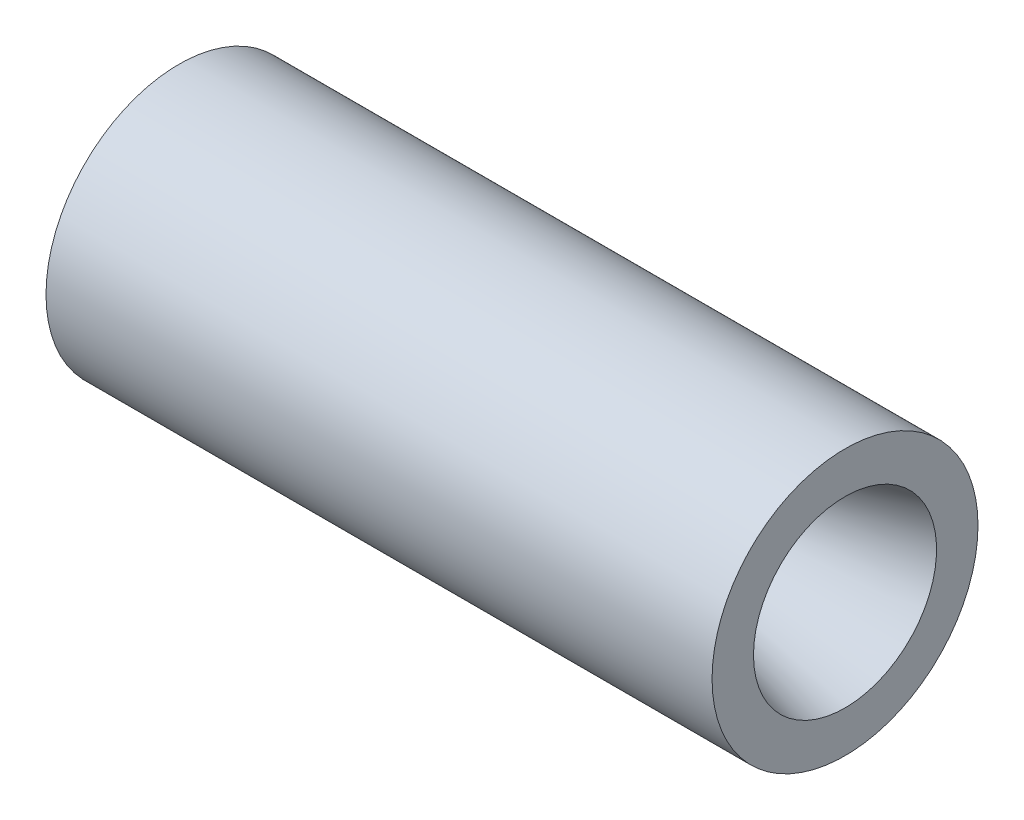
SolidWorks part; units mm, degrees
ref_plane "Front Plane" through (0, 0, 0) normal (0, 0, 1) x (1, 0, 0)
ref_plane "Top Plane" through (0, 0, 0) normal (0, 1, 0) x (1, 0, 0)
ref_plane "Right Plane" through (0, 0, 0) normal (1, 0, 0) x (0, 0, -1)
sketch "Sketch1" plane through (0, 0, 0) normal (0, 0, 1) x (1, 0, 0)
  line L0 (0, 0) -> (0, 43.2766) construction
  line L1 (0, 43.2766) -> (142.9669, 43.2766)
  line L2 (152.7031, 40.2068) -> (181.4981, 20.0443)
  line L3 (195.6276, 17.5529) -> (267.1743, 36.7237)
  line L4 (267.1743, 36.7237) -> (267.1743, 53.34)
  line L5 (267.1743, 53.34) -> (0, 53.34)
  line L6 (0, 53.34) -> (0, 43.2766)
  line L7 (0, 16.9745) -> (267.1743, 16.9745) construction
  line L8 (267.1743, 16.9745) -> (267.1743, 36.7237) construction
  line L9 (0, 0) -> (267.1743, 0) construction
  line L10 (267.1743, 0) -> (267.1743, 16.9745) construction
  arc A0 (142.9669, 43.2766) -> (152.7031, 40.2068) centre (142.9669, 26.3021) cw
  arc A1 (181.4981, 20.0443) -> (195.6276, 17.5529) centre (191.2343, 33.9489) ccw
  dimension "D5" = 16.9745
  dimension "D2" = 53.34
  dimension "D1" = 142.9669
  dimension "D3" = 43.2766
  dimension "D4" = 36.7237
  dimension "D6" = 16.9745
  dimension "D7" = 15
  dimension "D8" = 35
revolve "Revolve2" add sketch "Sketch1" angle 360 about L9
equation "\"D2@Sketch1\"=4.5/2-(.15)"
equation "\"D3@Sketch1\"=3.407604/2"
equation "\"D4@Sketch1\"=2.891633/2"
equation "\"D5@Sketch1\"=1.336572235/2"
equation "\"D6@Sketch1\"=\"D5@Sketch1\""
